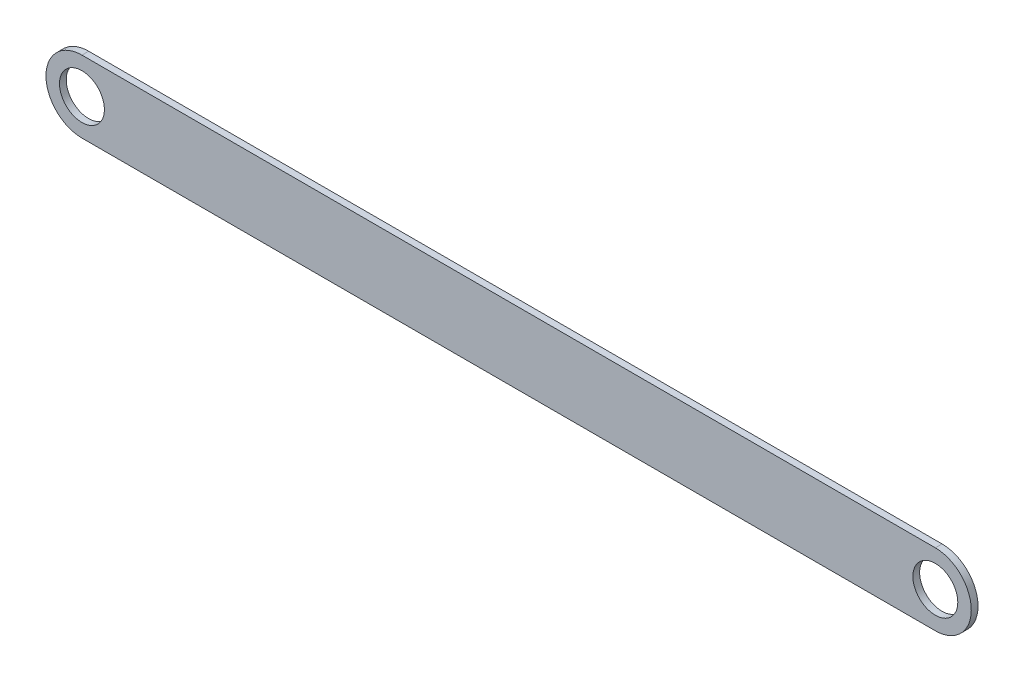
SolidWorks part; units mm, degrees
ref_plane "Front Plane" through (0, 0, 0) normal (0, 0, 1) x (1, 0, 0)
ref_plane "Top Plane" through (0, 0, 0) normal (0, 1, 0) x (1, 0, 0)
ref_plane "Right Plane" through (0, 0, 0) normal (1, 0, 0) x (0, 0, -1)
sketch "Sketch1" plane through (0, 0, 0) normal (0, 0, 1) x (1, 0, 0)
  line L0 (-95, 0) -> (95, 0) construction
  line L1 (-95, 8) -> (95, 8)
  line L2 (-95, -8) -> (95, -8)
  arc A0 (-95, 8) -> (-95, -8) centre (-95, 0) ccw
  arc A1 (95, -8) -> (95, 8) centre (95, 0) ccw
  circle A2 centre (-95, 0) radius 5
  circle A3 centre (95, 0) radius 5
  point P2 (0, 0)
  dimension "D3" = 10
  dimension "D4" = 10
  dimension "D1" = 190
  dimension "D2" = 16
extrude "Boss-Extrude1" add sketch "Sketch1" along normal blind 1.5
